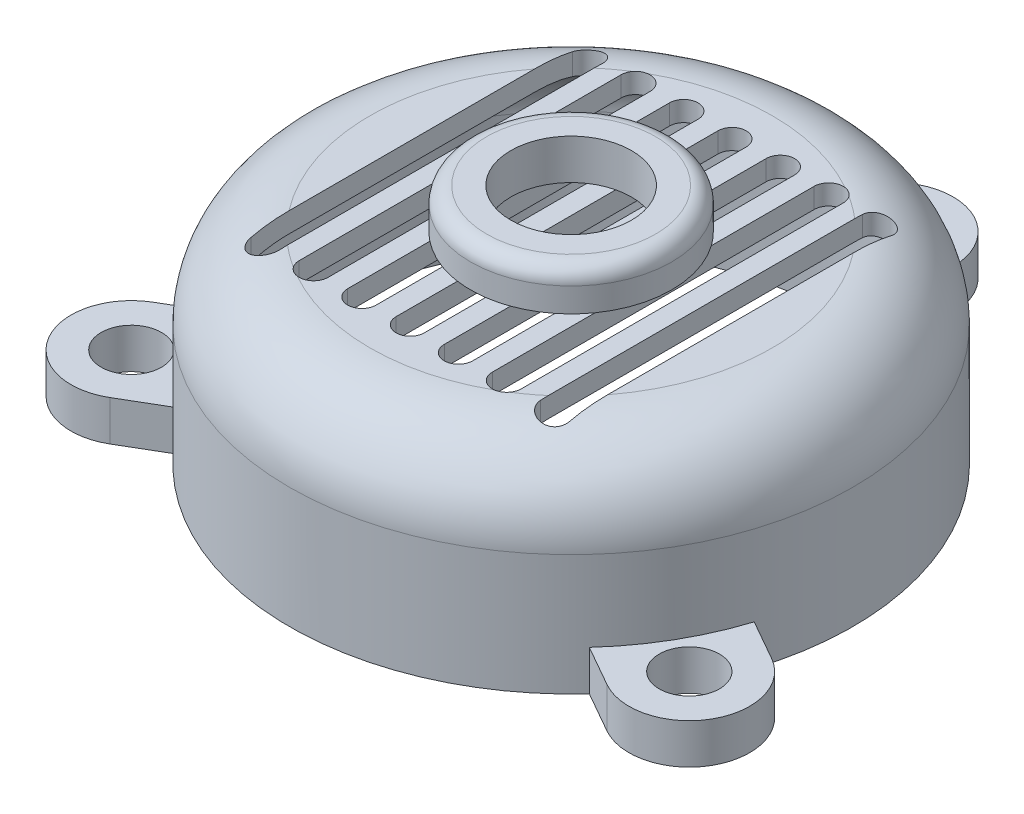
SolidWorks part; units mm, degrees
ref_plane "Front Plane" through (0, 0, 0) normal (0, 0, 1) x (1, 0, 0)
ref_plane "Top Plane" through (0, 0, 0) normal (0, 1, 0) x (1, 0, 0)
ref_plane "Right Plane" through (0, 0, 0) normal (1, 0, 0) x (0, 0, -1)
sketch "Sketch1" plane through (0, 0, 0) normal (0, 1, 0) x (1, 0, 0)
  circle A0 centre (0, 0) radius 3.5
  dimension "D1" = 7
extrude "Boss-Extrude1" add sketch "Sketch1" along normal mid plane 2.5
fillet "Fillet1" radius 1 1 edges at (0, 1.25, 3.5)
shell "Shell1" thickness 0.25
sketch "Sketch2" plane through (0, 1.25, 0) normal (0, 1, 0) x (1, 0, 0)
  line L0 (0, 2) -> (0, -2) construction
  line L1 (0.175, 2) -> (0.175, -2)
  line L2 (-0.175, 2) -> (-0.175, -2)
  line L3 (0.6, 2) -> (0.6, -2) construction
  line L4 (0.7768, 2) -> (0.7768, -2)
  line L5 (0.4232, 2) -> (0.4232, -2)
  line L6 (1.2, 2) -> (1.2, -2) construction
  line L7 (1.38, 2) -> (1.38, -2)
  line L8 (1.02, 2) -> (1.02, -2)
  line L9 (1.8, 2) -> (1.8, -2) construction
  line L10 (1.98, 2) -> (1.98, -2)
  line L11 (1.62, 2) -> (1.62, -2)
  arc A0 (0.175, 2) -> (-0.175, 2) centre (0, 2) ccw
  arc A1 (-0.175, -2) -> (0.175, -2) centre (0, -2) ccw
  arc A2 (0.7768, 2) -> (0.4232, 2) centre (0.6, 2) ccw
  arc A3 (0.4232, -2) -> (0.7768, -2) centre (0.6, -2) ccw
  arc A4 (1.38, 2) -> (1.02, 2) centre (1.2, 2) ccw
  arc A5 (1.02, -2) -> (1.38, -2) centre (1.2, -2) ccw
  arc A6 (1.98, 2) -> (1.62, 2) centre (1.8, 2) ccw
  arc A7 (1.62, -2) -> (1.98, -2) centre (1.8, -2) ccw
  point P3 (0, 0)
  point P10 (0.6, 0)
  point P15 (1.2, 0)
  point P22 (1.8, 0)
  dimension "D3" = 0.175
  dimension "D4" = 0.1768
  dimension "D5" = 0.18
  dimension "D6" = 0.18
  dimension "D7" = 0.6
  dimension "D1" = 4
  dimension "D2" = 2
  dimension "D8" = 0.6
  dimension "D9" = 0.6
extrude "Cut-Extrude2" cut sketch "Sketch2" against normal blind 10
mirror "Mirror1" about plane through (0, 0, 0) normal (1, 0, 0) of "Cut-Extrude2"
sketch "Sketch4" plane through (0, 1.25, 0) normal (0, 1, 0) x (1, 0, 0)
  circle A0 centre (0, 0) radius 1.25
  circle A1 centre (0, 0) radius 0.75
  dimension "D1" = 1.5
  dimension "D2" = 2.5
extrude "Boss-Extrude2" add sketch "Sketch4" along normal blind 0.5
fillet "Fillet2" radius 0.2 1 edges at (0, 1.75, 1.25)
sketch "Sketch5" plane through (0, -1.25, 0) normal (0, -1, 0) x (1, 0, 0)
  line L0 (3.8365, 1.3454) -> (3.3355, 1.0604)
  line L1 (3.8365, 1.3454) -> (3.3269, 1.0555) construction
  line L2 (-1007, 0) -> (-3.5, 0) construction
  line L3 (866.0254, 500) -> (-3.0311, -1.75) construction
  line L4 (3.0949, 2.6492) -> (2.5853, 2.3593)
  line L5 (0, 0) -> (50000, 0) construction
  line L6 (-3.5281, -2.0369) -> (-43301.2702, -25000) construction
  arc A0 (3.8365, 1.3454) -> (3.0949, 2.6492) centre (3.4657, 1.9973) ccw
  arc A1 (4.0739, 0) -> (3.0949, 2.6492) centre (0, 0) ccw construction
  circle A3 centre (0, 0) radius 3.5 construction
  circle A6 centre (3.4657, 1.9973) radius 0.375
  arc A7 (3.3355, 1.0604) -> (2.5853, 2.3593) centre (0, 0) ccw
  arc A8 (-4.0739, 0) -> (-3.5281, -2.0369) centre (0, 0) ccw construction
  circle M2 centre (0, 0) radius 3.5
  dimension "D1" = 1.5
  dimension "D2" = 4
  dimension "D3" = 0.7274
  dimension "D5" = 0.75
  dimension "D4" = 30
extrude "Boss-Extrude3" add sketch "Sketch5" against normal blind 0.5 contours L0 A0 L4 A6 M2
pattern_circular "CirPattern1" count 3 over 360 about axis through (0, 0, 0) along (0, 1, 0) of "Boss-Extrude3"
